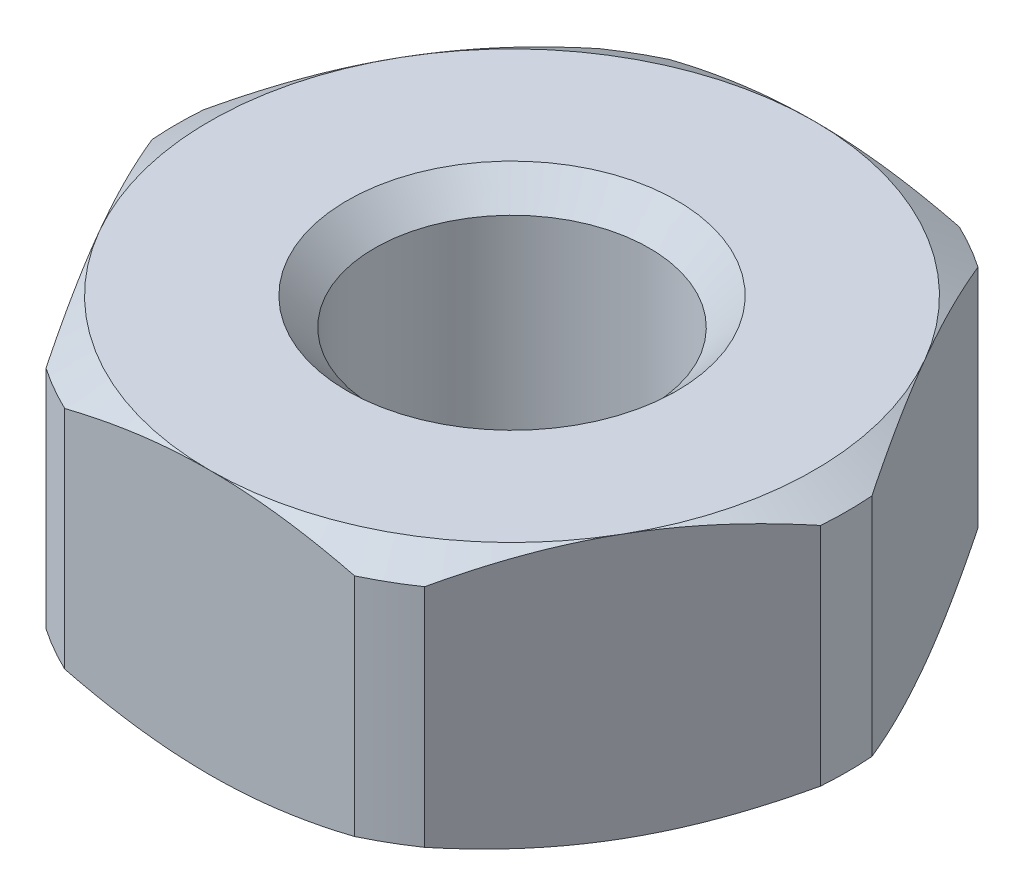
SolidWorks part; units mm, degrees
ref_plane "Front" through (0, 0, 0) normal (0, 0, 1) x (1, 0, 0)
ref_plane "Top" through (0, 0, 0) normal (0, 1, 0) x (1, 0, 0)
ref_plane "Right" through (0, 0, 0) normal (1, 0, 0) x (0, 0, -1)
sketch "Sketch1" plane through (0, 0, 0) normal (0, 1, 0) x (1, 0, 0)
  circle A0 centre (0, 0) radius 3.05
  dimension "D1" = 6.1
extrude "Boss-Extrude1" add sketch "Sketch1" along normal blind 2.4
sketch "Sketch2" plane through (0, 2.4, 0) normal (0, 1, 0) x (1, 0, 0)
  line L1 (1.5877, 2.75) -> (-1.5877, 2.75)
  line L2 (-1.5877, 2.75) -> (-3.1754, 0)
  line L3 (-3.1754, 0) -> (-1.5877, -2.75)
  line L4 (-1.5877, -2.75) -> (1.5877, -2.75)
  line L5 (1.5877, -2.75) -> (3.1754, 0)
  line L6 (3.1754, 0) -> (1.5877, 2.75)
  circle A0 centre (0, 0) radius 2.75 construction
  dimension "D1" = 5.5
extrude "Cut-Extrude1" cut sketch "Sketch2" against normal up to next (2.4 mm away) flip side to cut
sketch "Sketch3" plane through (0, 0, 0) normal (1, 0, 0) x (0, 0, -1)
  line L0 (0, 0) -> (0, 3.1318) construction
  line L1 (2.75, 2.4) -> (4, 2.4)
  line L2 (4, 2.4) -> (4, 1.6783)
  line L3 (4, 0) -> (2.75, 0)
  line L4 (2.75, 0) -> (4, 0.7217)
  line L5 (2.75, 2.4) -> (4, 1.6783)
  line L6 (2.5174, 0) -> (0.2326, 0) construction
  line L7 (4, 0.7217) -> (4, 0)
  dimension "D1" = 4
  dimension "D2" = 30
  dimension "D3" = 30
revolve "Cut-Revolve1" cut sketch "Sketch3" angle 360 about L0
hole_wizard "M3 Tapped Hole1" positions "Sketch5" profile "Sketch4" tap size "M3" standard "ISO" end condition up to next
sketch "Sketch5" plane through (0, 2.4, 0) normal (0, 1, 0) x (1, 0, 0)
  point P0 (0, 0)
sketch "Sketch4" plane through (0, 2.4, 0) normal (1, 0, 0) x (0, 0, 1)
  line L0 (0, 0) -> (0, 2.4)
  line L1 (0, 2.4) -> (1.25, 2.4)
  line L2 (1.25, 2.4) -> (1.25, 0)
  line L5 (1.25, 0) -> (0, 0)
  line L11 (0, -6.35) -> (0, 107.95) construction
  dimension "Thru Tap Drill Dia." = 2.5
  dimension "Thru Tap Drill Depth" = 2.4
cosmetic thread "Hole Thread1" parameters "D2"=3
chamfer "Chamfer1" distance 0.25 angle 45 2 edges at (0, 2.4, 1.25) (0, 0, 1.25)
